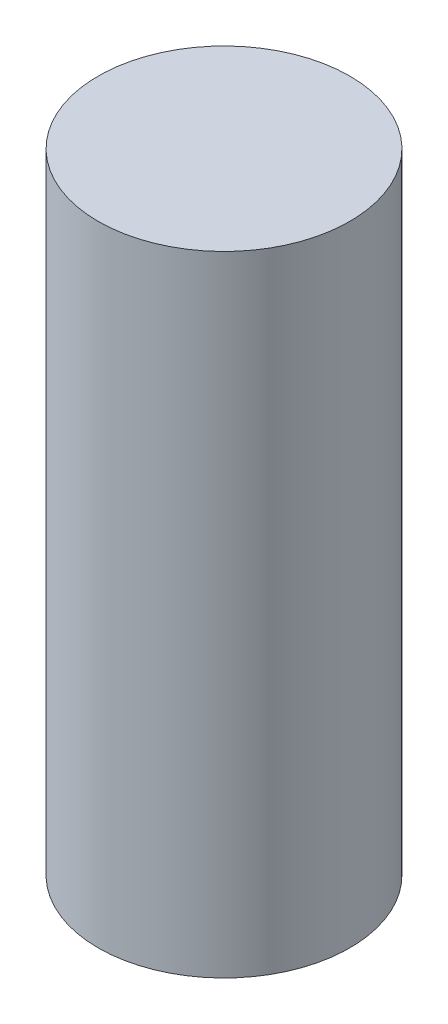
SolidWorks part; units mm, degrees
ref_plane "Front Plane" through (0, 0, 0) normal (0, 0, 1) x (1, 0, 0)
ref_plane "Top Plane" through (0, 0, 0) normal (0, 1, 0) x (1, 0, 0)
ref_plane "Right Plane" through (0, 0, 0) normal (1, 0, 0) x (0, 0, -1)
sketch "Sketch1" plane through (0, 0, 0) normal (0, 1, 0) x (1, 0, 0)
  circle A0 centre (0, 0) radius 4
  dimension "D1" = 8
extrude "coupling hieght" add sketch "Sketch1" along normal blind 20
